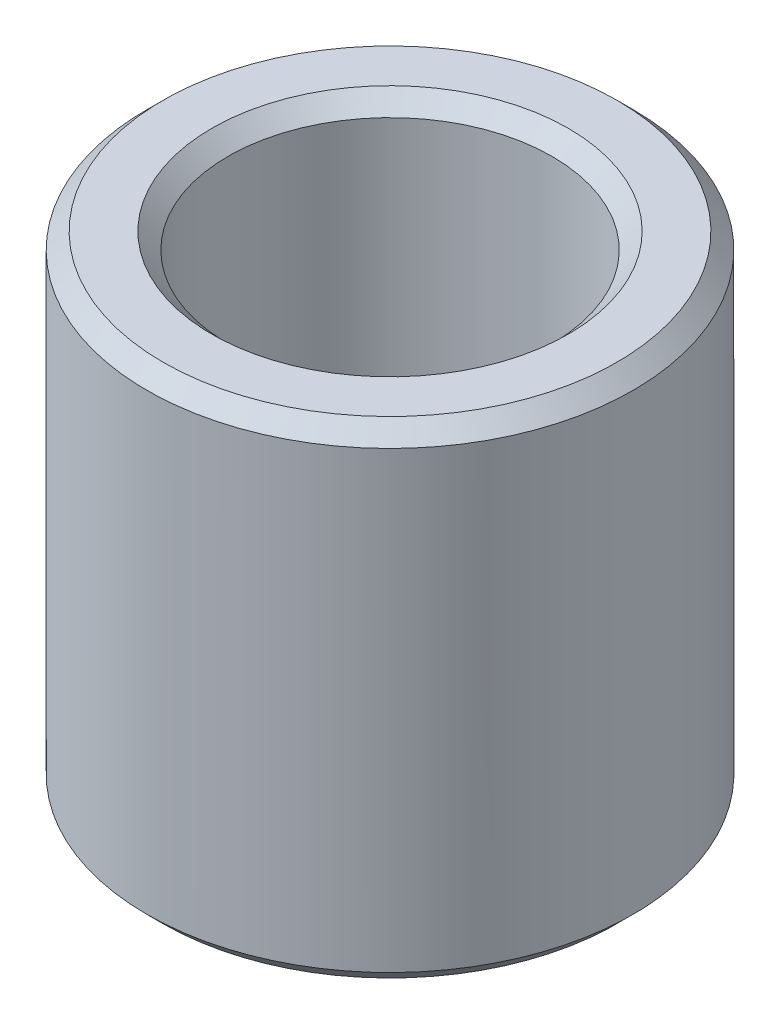
SolidWorks part; units mm, degrees
material "黄铜"
ref_plane "前视基准面" through (0, 0, 0) normal (0, 0, 1) x (1, 0, 0)
ref_plane "上视基准面" through (0, 0, 0) normal (0, 1, 0) x (1, 0, 0)
ref_plane "右视基准面" through (0, 0, 0) normal (1, 0, 0) x (0, 0, -1)
sketch "草图1" plane through (0, 0, 0) normal (0, 0, 1) x (1, 0, 0)
  line L0 (0, 0) -> (0, 3391.2556) construction
  line L2 (-3, -3) -> (-2, -3)
  line L3 (-3, -3) -> (-3, 3)
  line L4 (-3, 3) -> (-2, 3)
  line L5 (-2, -3) -> (-2, 3)
  line L6 (-3, -3) -> (-2, 3) construction
  line L7 (-3, 3) -> (-2, -3) construction
  point P3 (-2.5, 0)
  dimension "内径" = 4
  dimension "外径" = 6
  dimension "厚度" = 6
revolve "旋转1" add sketch "草图1" angle 360 about L0
chamfer "倒角1" distance 0.2 angle 45 4 edges at (0, -3, -2) (0, 3, -2) (0, 3, -3) (0, -3, -3)
